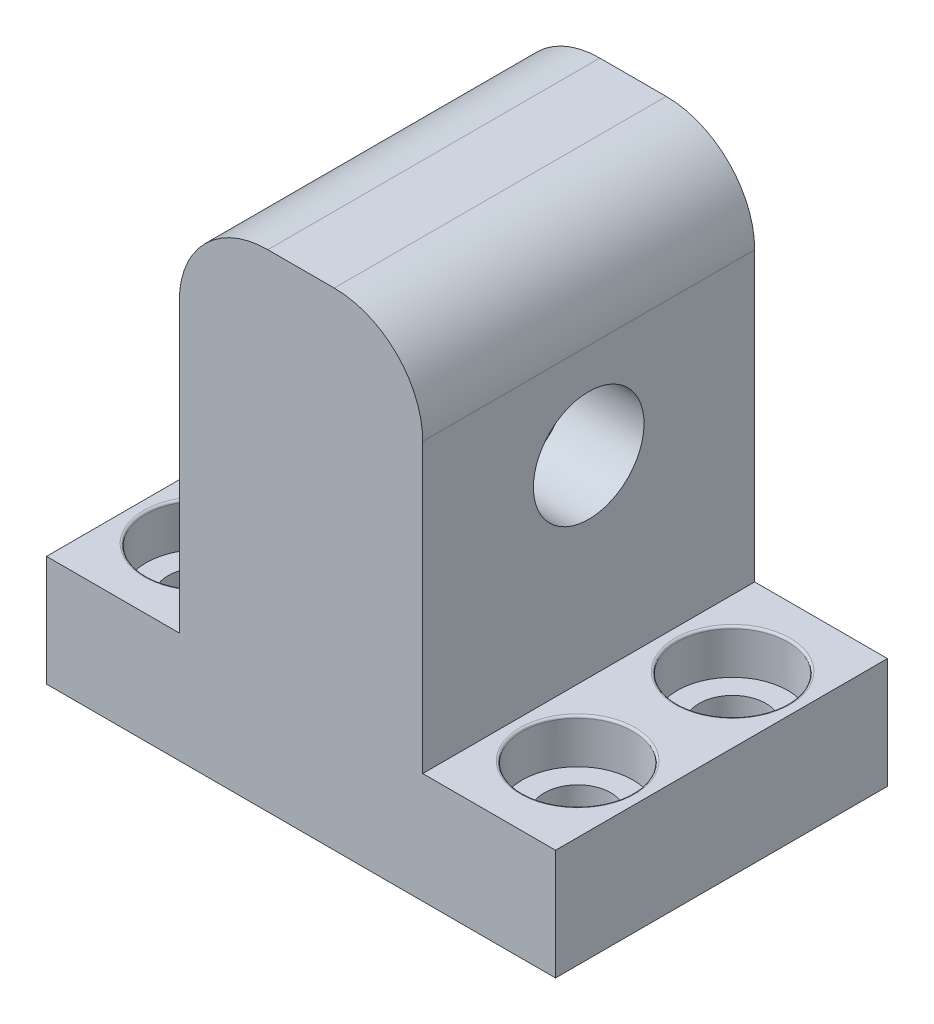
SolidWorks part; units mm, degrees
ref_plane "Alzado" through (0, 0, 0) normal (0, 0, 1) x (1, 0, 0)
ref_plane "Planta" through (0, 0, 0) normal (0, 1, 0) x (1, 0, 0)
ref_plane "Vista lateral" through (0, 0, 0) normal (1, 0, 0) x (0, 0, -1)
sketch "Croquis1" plane through (0, 0, 0) normal (0, 0, 1) x (1, 0, 0)
  line L0 (0, 11) -> (0, -11) construction
  line L1 (-1.5, 11) -> (1.5, 11)
  line L2 (-5.5, 7) -> (-5.5, -6)
  line L3 (-5.5, -11) -> (5.5, -11)
  line L4 (5.5, 7) -> (5.5, -6)
  line L5 (-5.5, 11) -> (5.5, -11) construction
  line L6 (-5.5, -11) -> (5.5, 11) construction
  line L7 (-5.5, -11) -> (-11.5, -11)
  line L9 (-5.5, -6) -> (-11.5, -6)
  line L10 (-11.5, -11) -> (-11.5, -6)
  line L11 (5.5, -6) -> (11.5, -6)
  line L12 (11.5, -11) -> (11.5, -6)
  line L13 (5.5, -11) -> (11.5, -11)
  arc A0 (5.5, 7) -> (1.5, 11) centre (1.5, 7) ccw
  arc A1 (-5.5, 7) -> (-1.5, 11) centre (-1.5, 7) cw
  point P0 (0, 0)
  dimension "D1" = 4
  dimension "D2" = 6
  dimension "D3" = 5
  dimension "D4" = 11
  dimension "D5" = 18
extrude "Saliente-Extruir1" add sketch "Croquis1" against normal blind 15
sketch "Croquis2" plane through (5.5, 0, 0) normal (1, 0, 0) x (0, 0, -1)
  line L0 (7.5, 11) -> (7.5, -6) construction
  line L1 (15, 11) -> (0, 11) construction
  line L2 (15, -6) -> (0, -6) construction
  line L3 (15, -11) -> (0, -11) construction
  circle A0 centre (7.5, 2.7) radius 2.5
  point P10 (0, 0)
  dimension "D2" = 5
  dimension "D1" = 13.7
extrude "Cortar-Extruir1" cut sketch "Croquis2" against normal blind 3.5
sketch "Croquis3" plane through (-5.5, 0, 0) normal (-1, 0, 0) x (0, 0, 1)
  line L0 (-7.5, 11) -> (-7.5, -6) construction
  line L1 (-15, 11) -> (0, 11) construction
  line L2 (-15, -6) -> (0, -6) construction
  line L3 (-15, -11) -> (0, -11) construction
  circle A0 centre (-7.5, 2.7) radius 2.5
  dimension "D2" = 5
  dimension "D1" = 13.7
extrude "Cortar-Extruir2" cut sketch "Croquis3" against normal blind 3.5
sketch "Croquis4" plane through (0, -6, 0) normal (0, 1, 0) x (1, 0, 0)
  line L0 (0, 15) -> (0, 0) construction
  line L1 (1.5, 15) -> (-1.5, 15) construction
  line L2 (-8.5, 15) -> (-8.5, 0) construction
  line L3 (-5.5, 15) -> (-11.5, 15) construction
  line L4 (-5.5, 0) -> (-11.5, 0) construction
  circle A0 centre (-8.5, 11) radius 2.5
  circle A1 centre (-8.5, 4) radius 2.5
  circle A2 centre (8.5, 4) radius 2.5
  circle A3 centre (8.5, 11) radius 2.5
  point P15 (0, 0)
  dimension "D1" = 5
  dimension "D2" = 4
  dimension "D3" = 4
extrude "Cortar-Extruir3" cut sketch "Croquis4" against normal blind 2
fillet "Redondeo1" radius 0.1 4 edges at (11, -6, -4) (11, -6, -11) (-11, -6, -4) (-11, -6, -11)
sketch "Croquis5" plane through (0, -6, 0) normal (0, 1, 0) x (1, 0, 0)
  line L0 (-8.5, 15) -> (-8.5, 0) construction
  line L1 (-5.5, 15) -> (-11.5, 15) construction
  line L2 (-5.5, 0) -> (-11.5, 0) construction
  line L3 (0, 15) -> (0, 0) construction
  line L4 (1.5, 15) -> (-1.5, 15) construction
  line L5 (1.5, 0) -> (-1.5, 0) construction
  circle A0 centre (-8.5, 11) radius 1.5
  circle A1 centre (-8.5, 4) radius 1.5
  circle A2 centre (-8.5, 11) radius 2.6 construction
  circle A3 centre (8.5, 4) radius 1.5
  circle A4 centre (8.5, 11) radius 1.5
  dimension "D1" = 3
extrude "Cortar-Extruir4" cut sketch "Croquis5" against normal through all
